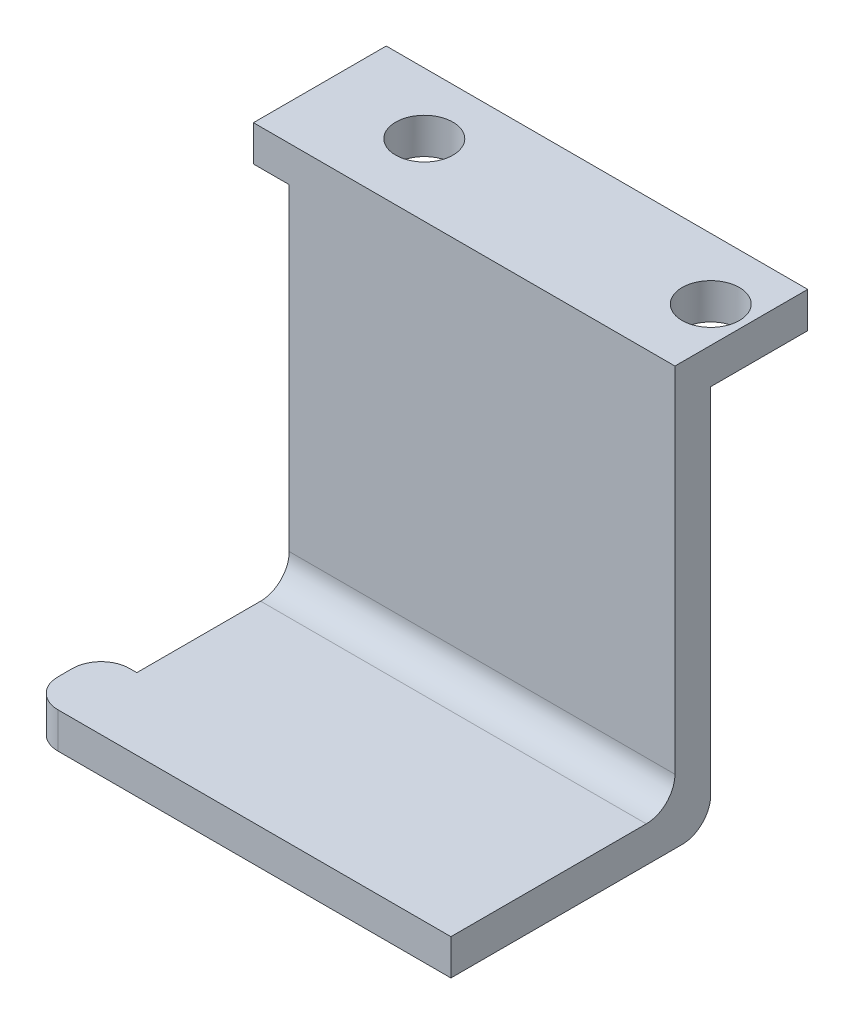
SolidWorks part; units mm, degrees
ref_plane "Front Plane" through (0, 0, 0) normal (0, 0, 1) x (1, 0, 0)
ref_plane "Top Plane" through (0, 0, 0) normal (0, 1, 0) x (1, 0, 0)
ref_plane "Right Plane" through (0, 0, 0) normal (1, 0, 0) x (0, 0, -1)
sketch "Sketch1" plane through (0, 0, 0) normal (0, 0, 1) x (1, 0, 0)
  line L1 (-18.6881, -16.9443) -> (18.6881, -16.9443)
  line L2 (-18.6881, -16.9443) -> (-18.6881, 16.9443)
  line L3 (-18.6881, 16.9443) -> (18.6881, 16.9443)
  line L4 (18.6881, -16.9443) -> (18.6881, 16.9443)
  line L5 (-18.6881, -16.9443) -> (18.6881, 16.9443) construction
  line L6 (-18.6881, 16.9443) -> (18.6881, -16.9443) construction
  point P0 (0, 0)
  dimension "D1" = 37.3761
  dimension "D2" = 33.8887
extrude "Boss-Extrude1" add sketch "Sketch1" along normal blind 3.175
sketch "Sketch2" plane through (0, 0, 0) normal (0, 0, -1) x (-1, 0, 0)
  line L0 (-18.6881, -16.9443) -> (-18.6881, 16.9443) construction
  line L1 (-18.6881, -13.7693) -> (18.688, -13.7693)
  line L2 (-18.6881, -13.7693) -> (-18.6881, -16.9443)
  line L3 (-18.6881, -16.9443) -> (18.6881, -16.9443)
  line L4 (18.688, -13.7693) -> (18.6881, -16.9443)
  line L5 (-18.6881, -13.7693) -> (18.6881, -16.9443) construction
  line L6 (-18.6881, -16.9443) -> (18.688, -13.7693) construction
  point P4 (0, -15.3568)
  dimension "D1" = 3.175
extrude "Boss-Extrude2" add sketch "Sketch2" against normal blind 23.0403
sketch "Sketch3" plane through (0, 0, 0) normal (0, 0, -1) x (-1, 0, 0)
  line L0 (18.6881, 16.9443) -> (18.6881, -16.9443) construction
  line L1 (-18.6881, 16.9443) -> (18.6881, 16.9443)
  line L2 (-18.6881, 16.9443) -> (-18.6881, 20.1193)
  line L3 (-18.6881, 20.1193) -> (18.6881, 20.1193)
  line L4 (18.6881, 16.9443) -> (18.6881, 20.1193)
  line L5 (-18.6881, 16.9443) -> (18.6881, 20.1193) construction
  line L6 (-18.6881, 20.1193) -> (18.6881, 16.9443) construction
  point P4 (0, 18.5318)
  dimension "D1" = 3.175
extrude "Boss-Extrude3" add sketch "Sketch3" along normal blind 8.6004 and the other way up to surface
sketch "Sketch4" plane through (0, 20.1193, 0) normal (0, 1, 0) x (1, 0, 0)
  line L0 (-18.6881, -3.175) -> (-18.6881, 8.6004) construction
  line L1 (-18.6881, -3.175) -> (18.6881, -3.175) construction
  circle A0 centre (-9.887, 3.175) radius 2.54
  circle A1 centre (15.513, 3.175) radius 2.54
  point P8 (11.0778, 1.4287)
  point P9 (15.513, 3.175)
  dimension "D1" = 8.8011
  dimension "D3" = 5.08
  dimension "D4" = 25.4
  dimension "D2" = 6.35
extrude "Cut-Extrude1" cut sketch "Sketch4" against normal through all
sketch "Sketch5" plane through (0, -13.7693, 0) normal (0, 1, 0) x (1, 0, 0)
  line L0 (-18.688, -23.0403) -> (18.6881, -23.0403) construction
  line L1 (-18.6881, -3.175) -> (-15.513, -3.175)
  line L2 (-18.6881, -3.175) -> (-18.6881, -16.6903)
  line L3 (-18.6881, -16.6903) -> (-15.513, -16.6903)
  line L4 (-15.513, -3.175) -> (-15.513, -16.6903)
  line L5 (-18.6881, -3.175) -> (-15.513, -16.6903) construction
  line L6 (-18.6881, -16.6903) -> (-15.513, -3.175) construction
  point P4 (-17.1005, -9.9327)
  dimension "D1" = 6.35
  dimension "D2" = 3.175
extrude "Cut-Extrude2" cut sketch "Sketch5" against normal through all
sketch "Sketch6" plane through (-15.513, 0, 0) normal (-1, 0, 0) x (0, 0, 1)
  line L1 (0, 16.9443) -> (3.175, 16.9443)
  line L2 (0, 16.9443) -> (0, -16.9443)
  line L3 (0, -16.9443) -> (3.175, -16.9443)
  line L4 (3.175, 16.9443) -> (3.175, -16.9443)
  line L5 (0, 16.9443) -> (3.175, -16.9443) construction
  line L6 (0, -16.9443) -> (3.175, 16.9443) construction
  point P4 (1.5875, 0)
extrude "Cut-Extrude3" cut sketch "Sketch6" along normal through all
fillet "Fillet1" radius 2.54 3 edges at (1.5875, -13.7693, 3.175) (-18.688, -15.3568, 23.0403) (-18.688, -15.3568, 16.6903)
fillet "Fillet2" radius 2.54 1 edges at (1.5875, -16.9443, 0)
